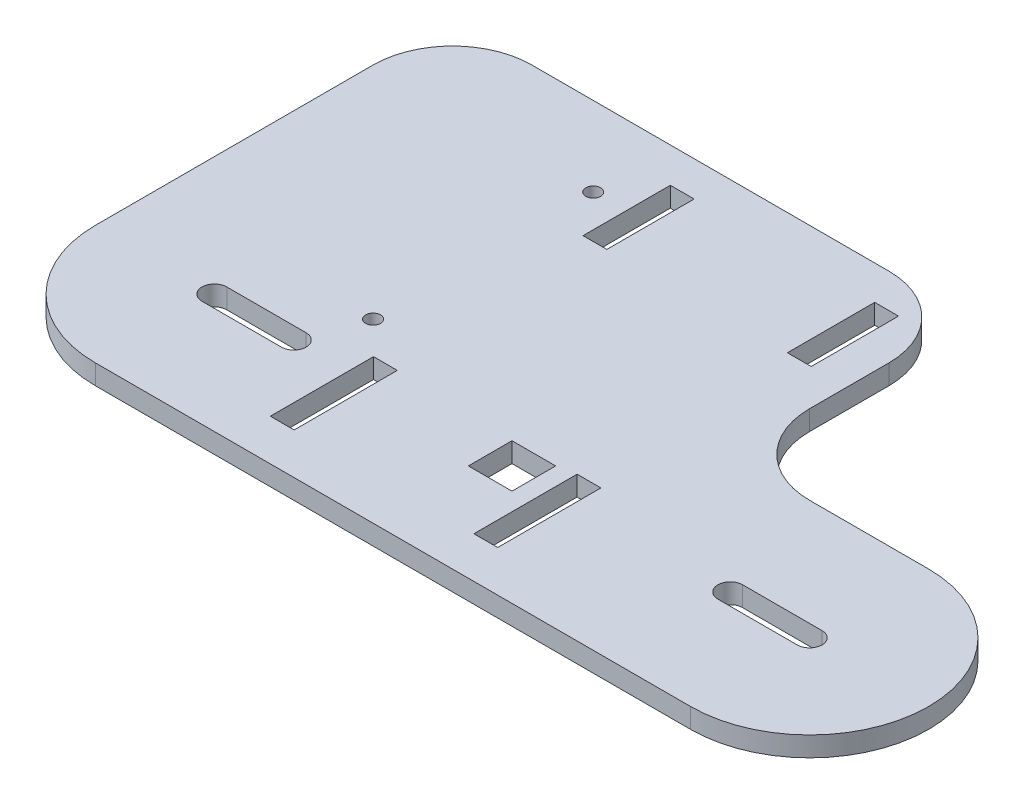
SolidWorks part; units mm, degrees
ref_plane "Front Plane" through (0, 0, 0) normal (0, 0, 1) x (1, 0, 0)
ref_plane "Top Plane" through (0, 0, 0) normal (0, 1, 0) x (1, 0, 0)
ref_plane "Right Plane" through (0, 0, 0) normal (1, 0, 0) x (0, 0, -1)
sketch "Sketch1" plane through (0, 0, 0) normal (0, 1, 0) x (1, 0, 0)
  line L0 (-6.985, -6.985) -> (6.985, -6.985)
  line L1 (6.985, -6.985) -> (6.985, 6.985)
  line L2 (6.985, 6.985) -> (-6.985, 6.985)
  line L3 (-6.985, 6.985) -> (-6.985, -6.985)
  line L4 (-95.25, -38.1) -> (95.25, -38.1)
  line L5 (95.25, 38.1) -> (57.15, 38.1)
  line L6 (31.75, 63.5) -> (31.75, 88.9)
  line L7 (6.35, 114.3) -> (-107.95, 114.3)
  line L8 (-133.35, 0) -> (-133.35, 88.9)
  line L9 (95.25, -3.9687) -> (69.85, -3.9687)
  line L10 (69.85, 3.9687) -> (95.25, 3.9687)
  line L11 (-95.25, -3.9687) -> (-69.85, -3.9687)
  line L12 (-69.85, 3.9687) -> (-95.25, 3.9687)
  arc A0 (95.25, -3.9687) -> (95.25, 3.9687) centre (95.25, 0) ccw
  arc A1 (-95.25, 3.9687) -> (-95.25, -3.9687) centre (-95.25, 0) ccw
  arc A2 (-133.35, 0) -> (-95.25, -38.1) centre (-95.25, 0) ccw
  arc A3 (95.25, -38.1) -> (95.25, 38.1) centre (95.25, 0) ccw
  arc A4 (-133.35, 88.9) -> (-107.95, 114.3) centre (-107.95, 88.9) cw
  arc A5 (6.35, 114.3) -> (31.75, 88.9) centre (6.35, 88.9) cw
  arc A6 (31.75, 63.5) -> (57.15, 38.1) centre (57.15, 63.5) ccw
  arc A7 (69.85, 3.9687) -> (69.85, -3.9687) centre (69.85, 0) ccw
  arc A8 (-69.85, -3.9687) -> (-69.85, 3.9687) centre (-69.85, 0) ccw
  point P22 (31.75, 114.3)
  point P25 (31.75, 38.1)
  dimension "D5" = 7.9375
  dimension "D6" = 7.9375
  dimension "D12" = 25.4
  dimension "D13" = 25.4
  dimension "D1" = 6.985
  dimension "D2" = 13.97
  dimension "D3" = 13.97
  dimension "D4" = 6.985
  dimension "D7" = 190.5
  dimension "D8" = 95.25
  dimension "D9" = 38.1
  dimension "D10" = 63.5
  dimension "D11" = 76.2
  dimension "D14" = 25.4
extrude "Boss-Extrude1" add sketch "Sketch1" along normal blind 6.35
sketch "Sketch2" plane through (0, 0, 0) normal (0, 1, 0) x (1, 0, 0)
  line L0 (-6.985, -6.985) -> (-6.985, 6.985)
  line L1 (-6.985, -6.985) -> (6.985, -6.985) construction
  line L2 (-6.985, 6.985) -> (6.985, 6.985)
  line L3 (6.985, 6.985) -> (6.985, -6.985)
  line L4 (6.985, -6.985) -> (-6.985, -6.985)
sketch "Sketch4" plane through (0, 6.35, 0) normal (0, 1, 0) x (1, 0, 0)
  line L0 (-95.25, -38.1) -> (95.25, -38.1) construction
  line L1 (20.32, -24.892) -> (12.7, -24.892)
  line L2 (20.32, -24.892) -> (20.32, 8.128)
  line L3 (20.32, 8.128) -> (12.7, 8.128)
  line L4 (12.7, -24.892) -> (12.7, 8.128)
  line L5 (31.75, 63.5) -> (31.75, 88.9) construction
  line L6 (-52.451, -24.892) -> (-44.831, -24.892)
  line L7 (-52.451, -24.892) -> (-52.451, 8.128)
  line L8 (-52.451, 8.128) -> (-44.831, 8.128)
  line L9 (-44.831, -24.892) -> (-44.831, 8.128)
  line L10 (20.32, 103.378) -> (12.7, 103.378)
  line L11 (20.32, 103.378) -> (20.32, 75.438)
  line L12 (20.32, 75.438) -> (12.7, 75.438)
  line L13 (12.7, 103.378) -> (12.7, 75.438)
  line L14 (-44.831, 103.124) -> (-52.451, 103.124)
  line L15 (-44.831, 103.124) -> (-44.831, 75.184)
  line L16 (-44.831, 75.184) -> (-52.451, 75.184)
  line L17 (-52.451, 103.124) -> (-52.451, 75.184)
  line L18 (6.35, 114.3) -> (-107.95, 114.3) construction
  circle A1 centre (-95.25, 0) radius 3.9687 construction
  dimension "D1" = 7.62
  dimension "D2" = 42.799
  dimension "D3" = 13.208
  dimension "D4" = 107.95
  dimension "D5" = 7.62
  dimension "D6" = 33.02
  dimension "D7" = 13.208
  dimension "D8" = 33.02
  dimension "D9" = 7.62
  dimension "D10" = 7.62
  dimension "D11" = 27.94
  dimension "D12" = 27.94
  dimension "D13" = 11.43
  dimension "D14" = 10.922
  dimension "D15" = 76.581
  dimension "D16" = 11.176
extrude "Cut-Extrude1" cut sketch "Sketch4" against normal through all
sketch "Sketch5" plane through (0, 6.35, 0) normal (0, 1, 0) x (1, 0, 0)
  line L0 (6.35, 114.3) -> (-107.95, 114.3) construction
  line L3 (31.75, 63.5) -> (31.75, 88.9) construction
  line L4 (31.75, 63.5) -> (31.75, 88.9) construction
  circle A0 centre (-62.9158, 88.9) radius 2.3812
  circle A1 centre (-62.9158, 18.4558) radius 2.3812
  point P4 (31.75, 76.2)
  dimension "D1" = 4.7625
  dimension "D4" = 4.7625
  dimension "D2" = 25.4
  dimension "D3" = 94.6658
  dimension "D5" = 95.8442
  dimension "D6" = 94.6658
extrude "Cut-Extrude2" cut sketch "Sketch5" against normal through all
equation "\"D4@Sketch1\"=\"D3@Sketch1\"/2"
equation "\"D1@Sketch1\"=\"D4@Sketch1\""
equation "\"D8@Sketch1\"=\"D7@Sketch1\"/2"
